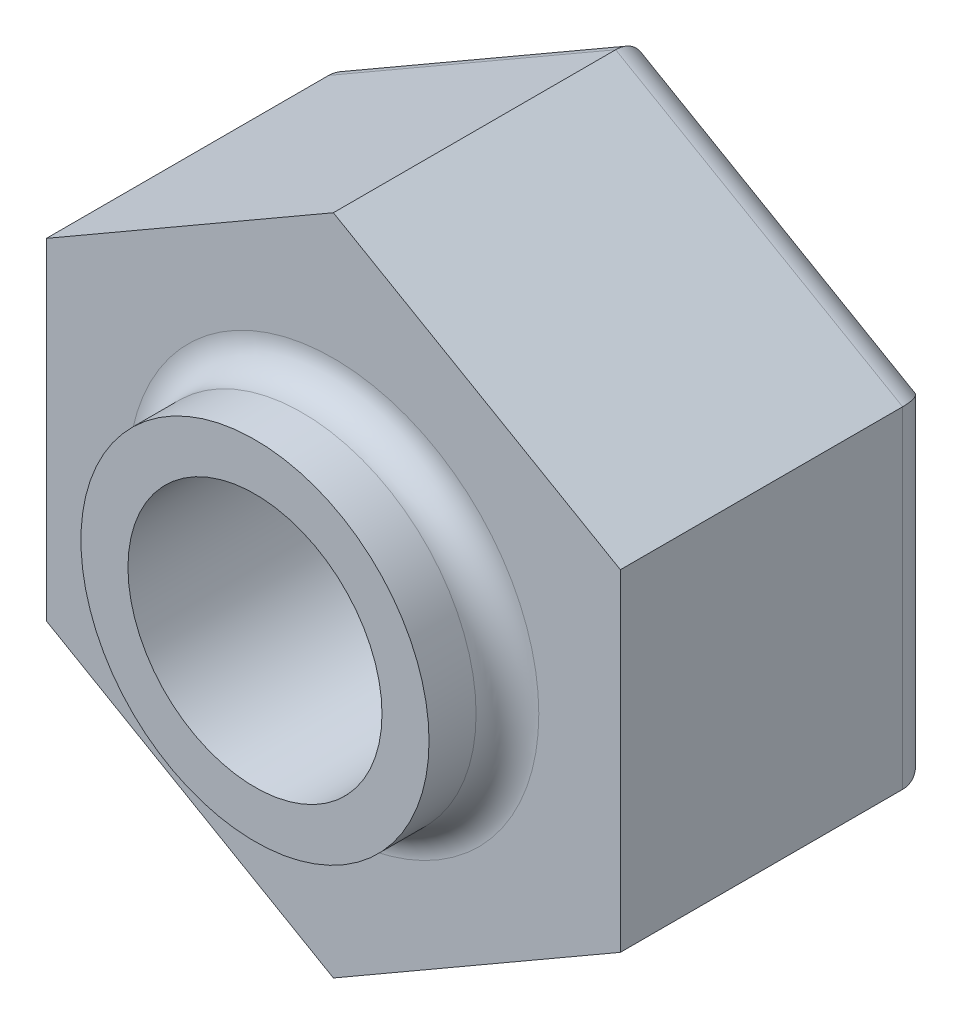
SolidWorks part; units mm, degrees
ref_plane "Front Plane" through (0, 0, 0) normal (0, 0, 1) x (1, 0, 0)
ref_plane "Top Plane" through (0, 0, 0) normal (0, 1, 0) x (1, 0, 0)
ref_plane "Right Plane" through (0, 0, 0) normal (1, 0, 0) x (0, 0, -1)
sketch "Sketch1" plane through (0, 0, 0) normal (0, 0, 1) x (1, 0, 0)
  line L1 (9.15, -5.2828) -> (9.15, 5.2828)
  line L2 (9.15, 5.2828) -> (0, 10.5655)
  line L3 (0, 10.5655) -> (-9.15, 5.2828)
  line L4 (-9.15, 5.2828) -> (-9.15, -5.2828)
  line L5 (-9.15, -5.2828) -> (0, -10.5655)
  line L6 (0, -10.5655) -> (9.15, -5.2828)
  circle A0 centre (0, 0) radius 9.15 construction
  circle A1 centre (0, 0) radius 4.05
  dimension "D1" = 18.3
  dimension "D2" = 8.1
extrude "Boss-Extrude1" add sketch "Sketch1" along normal blind 10
sketch "Sketch2" plane through (0, 0, 10) normal (0, 0, 1) x (1, 0, 0)
  circle A0 centre (0, 0) radius 5.55
  circle A1 centre (0, 0) radius 4.05 construction
  circle M7 centre (0, 0) radius 4.05
  dimension "D1" = 1.5
extrude "Boss-Extrude2" add sketch "Sketch2" along normal blind 2.5 contours A0 M7
fillet "Fillet1" radius 1 8 edges at (5.55, 0, 10) (4.05, 0, 0) (9.15, 0, 0) (4.575, 7.9241, 0) (-4.575, 7.9241, 0) (-9.15, 0, 0) (-4.575, -7.9241, 0) (4.575, -7.9241, 0)
